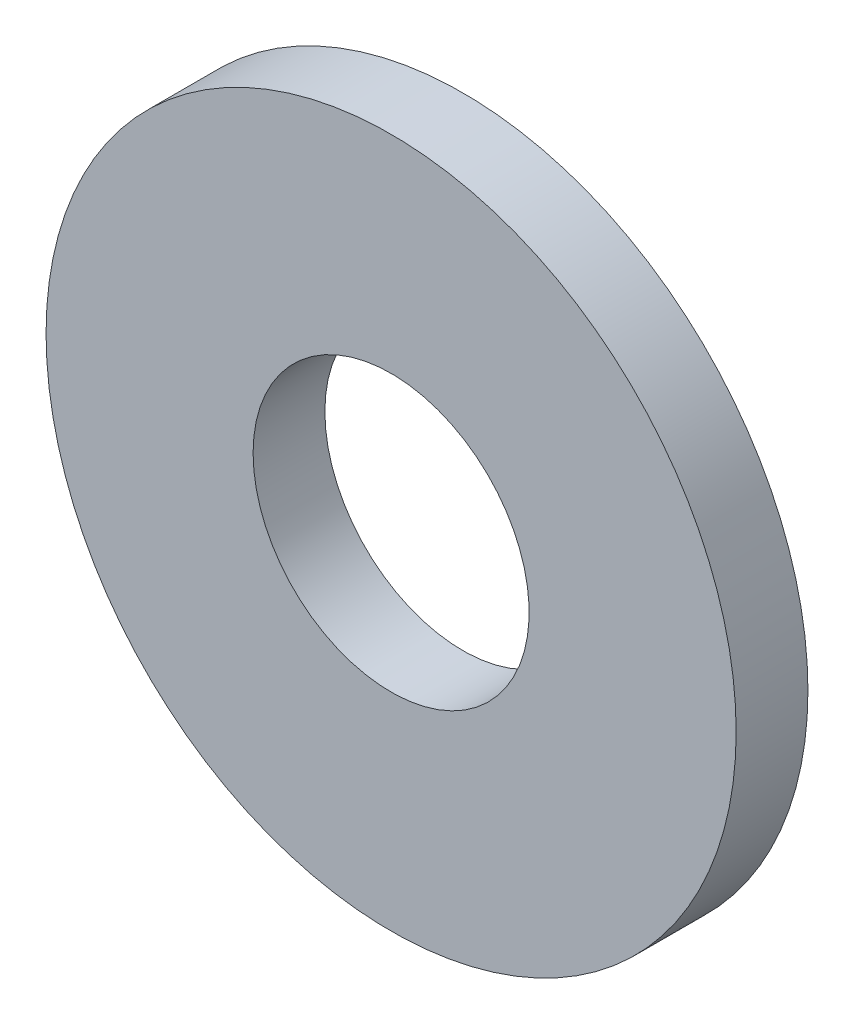
SolidWorks part; units mm, degrees
ref_plane "Front Plane" through (0, 0, 0) normal (0, 0, 1) x (1, 0, 0)
ref_plane "Top Plane" through (0, 0, 0) normal (0, 1, 0) x (1, 0, 0)
ref_plane "Right Plane" through (0, 0, 0) normal (1, 0, 0) x (0, 0, -1)
sketch "Sketch1" plane through (0, 0, 0) normal (0, 0, 1) x (1, 0, 0)
  circle A0 centre (0, 0) radius 3.175
  circle A1 centre (0, 0) radius 7.9375
  dimension "D1" = 6.35
  dimension "D2" = 15.875
extrude "Boss-Extrude1" add sketch "Sketch1" along normal blind 1.651
